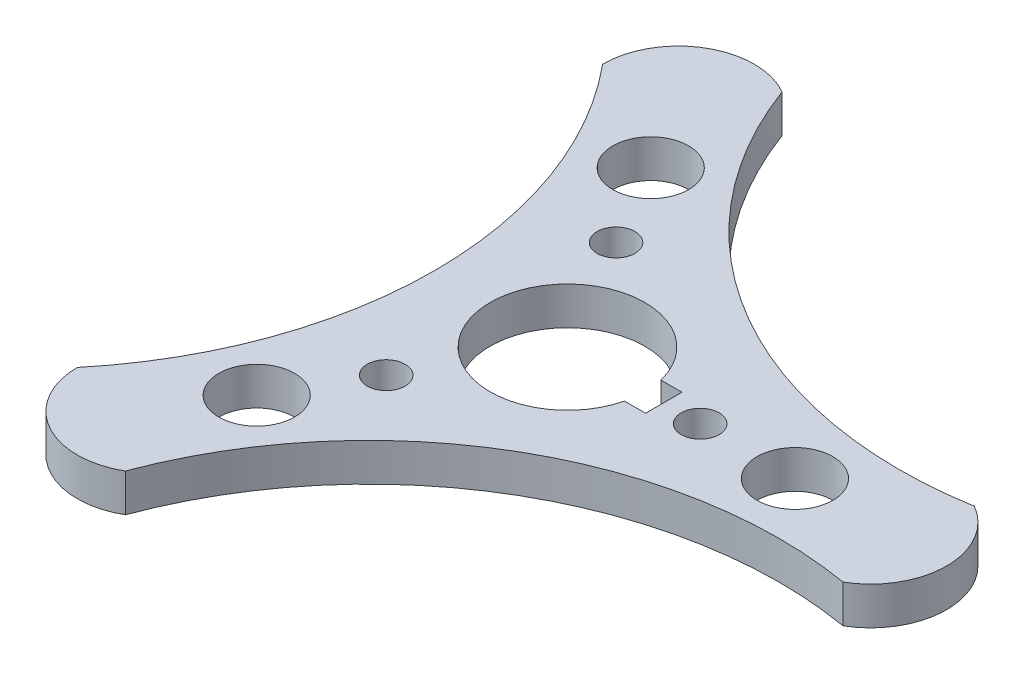
SolidWorks part; units mm, degrees
ref_plane "Front Plane" through (0, 0, 0) normal (0, 0, 1) x (1, 0, 0)
ref_plane "Top Plane" through (0, 0, 0) normal (0, 1, 0) x (1, 0, 0)
ref_plane "Right Plane" through (0, 0, 0) normal (1, 0, 0) x (0, 0, -1)
sketch "Sketch1" plane through (0, 0, 0) normal (0, 1, 0) x (1, 0, 0)
  line L0 (-9.525, 16.4978) -> (0, 21.997) construction
  line L1 (28.575, 5.4993) -> (-9.525, 27.4963)
  line L2 (-19.05, 21.997) -> (-19.05, -21.997)
  line L3 (-9.525, -27.4963) -> (28.575, -5.4993)
  line L4 (19.05, 0) -> (-9.525, 16.4978)
  line L5 (-9.525, 16.4978) -> (-9.525, -16.4978)
  line L6 (-9.525, -16.4978) -> (19.05, 0)
  line L7 (-8.0658, 1.5232) -> (8.0658, 1.5232)
  line L8 (-8.0658, 1.5232) -> (-8.0658, -1.5232)
  line L9 (-8.0658, -1.5232) -> (8.0658, -1.5232)
  line L10 (8.0658, 1.5232) -> (8.0658, -1.5232)
  line L11 (-8.0658, 1.5232) -> (8.0658, -1.5232) construction
  line L12 (-8.0658, -1.5232) -> (8.0658, 1.5232) construction
  line L13 (0, 21.997) -> (-19.05, 10.9985) construction
  line L14 (-9.525, -16.4978) -> (0, -21.997)
  line L15 (0, -21.997) -> (-19.05, -10.9985)
  line L16 (19.05, 0) -> (19.05, 10.9985) construction
  line L17 (19.05, 10.9985) -> (19.05, -10.9985) construction
  line L19 (11.1125, 0) -> (-5.5563, 9.6237)
  line L20 (-5.5563, 9.6237) -> (-5.5563, -9.6237)
  line L21 (-5.5563, -9.6237) -> (11.1125, 0)
  circle A0 centre (0, 0) radius 38.1 construction
  circle A1 centre (0, 0) radius 6.4802
  circle A2 centre (0, 0) radius 19.05 construction
  circle A3 centre (-9.525, 16.4978) radius 3.175
  circle A4 centre (-9.525, -16.4978) radius 3.175
  circle A5 centre (19.05, 0) radius 3.175
  circle A6 centre (0, 0) radius 11.1125 construction
  circle A7 centre (11.1125, 0) radius 1.5875
  circle A8 centre (-5.5563, 9.6237) radius 1.5875
  circle A9 centre (-5.5563, -9.6237) radius 1.5875
  arc A10 (-19.05, -21.997) -> (-9.525, -27.4963) centre (-12.7, -21.997) ccw
  arc A11 (28.575, 5.4993) -> (28.575, -5.4993) centre (25.4, 0) cw
  arc A12 (-9.525, 27.4963) -> (-19.05, 21.997) centre (-12.7, 21.997) ccw
  arc A13 (-19.05, -21.997) -> (-19.05, 21.997) centre (-45.5613, 0) ccw
  arc A14 (-9.525, 27.4963) -> (28.575, 5.4993) centre (22.7806, 39.4572) ccw
  arc A15 (-9.525, -27.4963) -> (28.575, -5.4993) centre (22.7806, -39.4572) cw
  point P33 (-19.05, -32.9956)
  dimension "D1" = 6.35
extrude "Boss-Extrude2" add sketch "Sketch1" along normal blind 3.175 contours L15 A15 A11 A14 A12 A13 A4 L5 A3 L4 A5 L6 | A10 A15 L15 A4 A13 | A5 L4 A3 L5 A4 L6 A9 L20 A1 L9 L8 L7 A8 L19 A7 L21 | A8 L20 A1 L19 | A9 L21 A1 L20 | A7 L19 A1 L7 L10 L9 L21 | A1 L7 L8 L9
